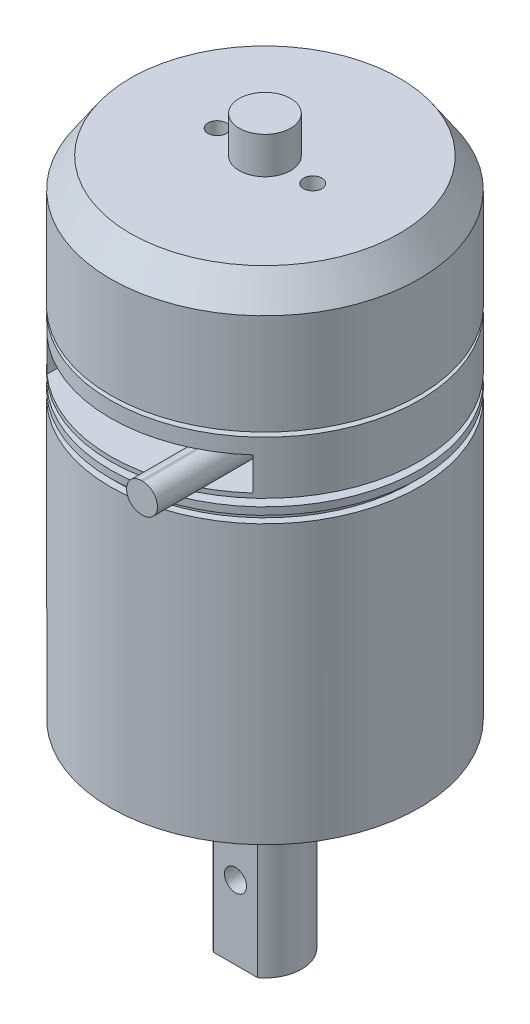
SolidWorks part; units mm, degrees
ref_plane "前视基准面" through (0, 0, 0) normal (0, 0, 1) x (1, 0, 0)
ref_plane "上视基准面" through (0, 0, 0) normal (0, 1, 0) x (1, 0, 0)
ref_plane "右视基准面" through (0, 0, 0) normal (1, 0, 0) x (0, 0, -1)
sketch "草图1" plane through (0, 0, 0) normal (0, 0, 1) x (1, 0, 0)
  line L0 (0, 0) -> (4.1, 0)
  line L1 (4.1, 0) -> (4.1, 6.7)
  line L2 (4.1, 6.7) -> (13.4, 6.7)
  line L3 (13.4, 6.7) -> (13.4, 8.7)
  line L4 (13.4, 8.7) -> (21, 8.7)
  line L5 (21, 8.7) -> (21, 10.2)
  line L6 (21, 10.2) -> (20, 10.2)
  line L7 (20, 10.2) -> (20, 11.2)
  line L8 (20, 11.2) -> (21, 11.2)
  line L9 (21, 11.2) -> (21, 12.2)
  line L10 (21, 12.2) -> (10, 12.2)
  line L11 (10, 12.2) -> (10, 13.2)
  line L12 (10, 13.2) -> (21, 13.2)
  line L13 (21, 13.2) -> (21, 20.4)
  line L14 (21, 20.4) -> (5, 20.4)
  line L15 (5, 20.4) -> (5, 21)
  line L16 (5, 21) -> (21, 21)
  line L17 (21, 21) -> (21, 34.7)
  line L18 (21, 34.7) -> (18.3, 38.7)
  line L19 (18.3, 38.7) -> (3.5, 38.7)
  line L20 (3.5, 38.7) -> (3.5, 43.7)
  line L21 (3.5, 43.7) -> (0, 43.7)
  line L22 (0, 43.7) -> (0, 0) construction
  line L23 (0, 0) -> (0, 43.7)
  dimension "D1" = 8.2
  dimension "D2" = 26.8
  dimension "D3" = 42
  dimension "D4" = 10
  dimension "D5" = 1.5
  dimension "D6" = 1
  dimension "D7" = 1
  dimension "D8" = 20
  dimension "D9" = 1
  dimension "D10" = 7.2
  dimension "D11" = 0.6
  dimension "D12" = 13.7
  dimension "D13" = 5
  dimension "D14" = 2
  dimension "D15" = 6.7
  dimension "D16" = 1
  dimension "D17" = 7
  dimension "D18" = 36.6
  dimension "D19" = 4
  dimension "D20" = 30
revolve "旋转1" add sketch "草图1" angle 360 about L22
ref_plane "基准面1" through (0, 0, 21) normal (0, 0, 1) x (1, 0, 0)
sketch "草图2" plane through (0, 0, 21) normal (0, 0, 1) x (1, 0, 0)
  line L1 (-14, 18.3) -> (14, 18.3)
  line L2 (-14, 18.3) -> (-14, 13.8)
  line L3 (-14, 13.8) -> (14, 13.8)
  line L4 (14, 18.3) -> (14, 13.8)
  line L5 (-14, 18.3) -> (14, 13.8) construction
  line L6 (-14, 13.8) -> (14, 18.3) construction
  line L7 (-21, 13.2) -> (21, 13.2) construction
  point P0 (0, 16.05)
  dimension "D1" = 28
  dimension "D2" = 4.5
  dimension "D3" = 0.6
extrude "切除-拉伸1" cut sketch "草图2" against normal blind 10
sketch "草图3" plane through (0, 0, 11) normal (0, 0, 1) x (1, 0, 0)
  line L0 (9.1851, 16.0532) -> (9.3851, 16.0532) construction
  line L1 (9.1851, 18.0532) -> (9.3851, 18.0532)
  line L2 (9.1851, 14.0532) -> (9.3851, 14.0532)
  arc A0 (9.1851, 18.0532) -> (9.1851, 14.0532) centre (9.1851, 16.0532) ccw
  arc A1 (9.3851, 14.0532) -> (9.3851, 18.0532) centre (9.3851, 16.0532) ccw
  point P2 (9.2851, 16.0532)
  dimension "D1" = 4
  dimension "D2" = 0.2
extrude "凸台-拉伸1" add sketch "草图3" along normal blind 15
hole_wizard "M3 螺纹孔1" positions "草图5" profile "草图6" tap size "M3" standard "GB"
sketch "草图5" plane through (0, 38.7, 0) normal (0, 1, 0) x (1, 0, 0)
  line L0 (0, 0) -> (0, 8.0606) construction
  point P0 (-6.5, 0)
  point P2 (6.5, 0)
  dimension "D1" = 13
sketch "草图6" plane through (-6.5, 38.7, 0) normal (1, 0, 0) x (0, 0, 1)
  line L0 (0, 0) -> (0, 4.7511)
  line L1 (0, 4.7511) -> (1.25, 4)
  line L2 (1.25, 4) -> (1.25, 0)
  line L5 (1.25, 0) -> (0, 0)
  line L10 (0, 4.7511) -> (-1.25, 4) construction
  line L11 (0, -6.35) -> (0, 107.95) construction
  dimension "螺纹孔钻头直径" = 2.5
  dimension "螺纹孔钻头深度" = 4
  dimension "导头角度" = 118
cosmetic thread "孔螺蚊线1" parameters "D1"=3.5, "D2"=3
cosmetic thread "孔螺蚊线2" parameters "D1"=3.5, "D2"=3
sketch "草图7" plane through (0, 0, 0) normal (0, 0, 1) x (1, 0, 0)
  line L0 (0, 8.7) -> (0, -54.6) construction
  line L1 (-13.4, 8.7) -> (13.4, 8.7) construction
  line L2 (0, -54.6) -> (5, -54.6)
  line L3 (5, -54.6) -> (5, -30.5)
  line L4 (5, -30.5) -> (8.275, -30.5)
  line L5 (13, -29.6) -> (13, -27.6)
  line L6 (13, -27.6) -> (21, -27.6)
  line L7 (21, -27.6) -> (21, 8.7)
  line L8 (-21, 8.7) -> (21, 8.7) construction
  line L9 (21, 8.7) -> (0, 8.7)
  line L10 (18.3, 38.7) -> (-18.3, 38.7) construction
  line L11 (13, -29.6) -> (8.275, -29.6)
  line L12 (8.275, -29.6) -> (8.275, -30.5)
  line L13 (0, 8.7) -> (0, -54.6)
  dimension "D1" = 66.3
  dimension "D2" = 2
  dimension "D3" = 0.9
  dimension "D4" = 27
  dimension "D5" = 26
  dimension "D6" = 10
  dimension "D7" = 16.55
revolve "旋转2" add sketch "草图7" angle 360 about L0
sketch "草图8" plane through (0, -54.6, 0) normal (0, -1, 0) x (1, 0, 0)
  line L0 (-3, 4) -> (3, 4)
  circle A0 centre (0, 0) radius 5 construction
  circle A1 centre (0, 0) radius 5 construction
  arc A2 (3, 4) -> (-3, 4) centre (0, 0) ccw
  dimension "D1" = 4
extrude "切除-拉伸2" cut sketch "草图8" against normal blind 20
hole_wizard "M4 螺纹孔1" positions "草图10" profile "草图9" tap size "M4" standard "GB"
sketch "草图10" plane through (0, -27.6, 0) normal (0, -1, 0) x (-1, 0, 0)
  circle A0 centre (0, 0) radius 17.5
  point P5 (0, -17.5)
  point P7 (-17.5, 0)
  point P9 (0, 17.5)
  point P11 (17.5, 0)
  dimension "D1" = 35
sketch "草图9" plane through (0, -27.6, 17.5) normal (1, 0, 0) x (0, 0, -1)
  line L0 (0, 0) -> (0, 11.0914)
  line L1 (0, 11.0914) -> (1.65, 10.1)
  line L2 (1.65, 10.1) -> (1.65, 0)
  line L5 (1.65, 0) -> (0, 0)
  line L10 (0, 11.0914) -> (-1.65, 10.1) construction
  line L11 (0, -6.35) -> (0, 107.95) construction
  dimension "螺纹孔钻头直径" = 3.3
  dimension "螺纹孔钻头深度" = 10.1
  dimension "导头角度" = 118
cosmetic thread "孔螺蚊线3" parameters "D1"=8, "D2"=4
cosmetic thread "孔螺蚊线4" parameters "D1"=8, "D2"=4
cosmetic thread "孔螺蚊线5" parameters "D1"=8, "D2"=4
cosmetic thread "孔螺蚊线6" parameters "D1"=8, "D2"=4
sketch "草图11" plane through (0, 0, 4) normal (0, 0, 1) x (1, 0, 0)
  line L0 (0, -54.6) -> (0, -44.6) construction
  line L1 (0, -54.6) -> (0, -34.6) construction
  line L2 (-3, -54.6) -> (3, -54.6) construction
  circle A0 centre (0, -44.6) radius 1.5
  dimension "D2" = 3
  dimension "D1" = 10
extrude "切除-拉伸3" cut sketch "草图11" against normal through all both and the other way through all
hole_wizard "M4 螺纹孔2" positions "3D草图1" profile "草图14" tap size "M4" standard "GB"
sketch3d "3D草图1"
  line L0 (0, -54.6, 0) -> (0, -34.6, 0) construction
  point P0 (0, -54.6, 0)
sketch "草图14" plane through (0, -54.6, 0) normal (1, 0, 0) x (0, 0, -1)
  line L0 (0, 0) -> (0, 6.9914)
  line L1 (0, 6.9914) -> (1.65, 6)
  line L2 (1.65, 6) -> (1.65, 0)
  line L5 (1.65, 0) -> (0, 0)
  line L10 (0, 6.9914) -> (-1.65, 6) construction
  line L11 (0, -6.35) -> (0, 107.95) construction
  dimension "螺纹孔钻头直径" = 3.3
  dimension "螺纹孔钻头深度" = 6
  dimension "导头角度" = 118
cosmetic thread "孔螺蚊线7" parameters "D1"=6, "D2"=4
